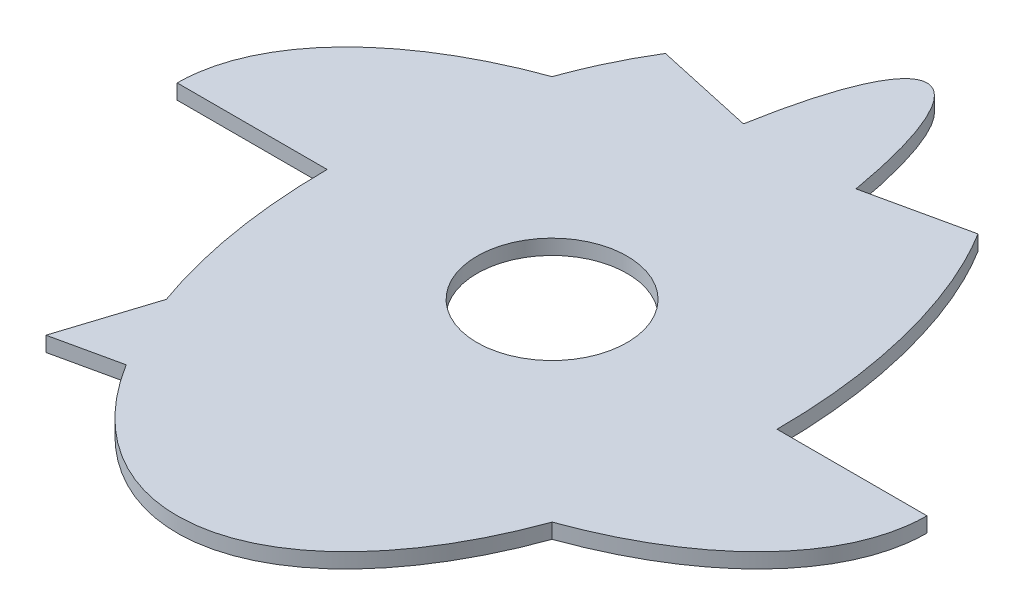
SolidWorks part; units mm, degrees
material "1.4016 (X6Cr17)"
ref_plane "Płaszczyzna przednia" through (0, 0, 0) normal (0, 0, 1) x (1, 0, 0)
ref_plane "Płaszczyzna górna" through (0, 0, 0) normal (0, 1, 0) x (1, 0, 0)
ref_plane "Płaszczyzna prawa" through (0, 0, 0) normal (1, 0, 0) x (0, 0, -1)
sketch "Szkic1" plane through (0, 0, 0) normal (0, 1, 0) x (1, 0, 0)
  line L0 (-61.0765, 17.9546) -> (45.7753, 41.4402)
  line L1 (-50, 0) -> (50, 0)
  line L2 (0, 50) -> (0, -50)
  line L3 (61.0765, 17.9546) -> (-45.7753, 41.4402)
  line L4 (-61.0765, -17.9546) -> (45.7753, -41.4402)
  line L5 (61.0765, -17.9546) -> (-45.7753, -41.4402)
  line L6 (34.2973, 52.5744) -> (-2.1147, -61.4701)
  line L7 (-34.2973, 52.5744) -> (2.1147, -61.4701)
  line L8 (34.2973, -52.5744) -> (-2.1147, 61.4701)
  line L9 (-34.2973, -52.5744) -> (2.1147, 61.4701)
  circle A0 centre (0, 0) radius 50
  circle A1 centre (0, 0) radius 30
  circle A2 centre (0, 0) radius 10
  ellipse E0 centre (0, 0) end of major axis (0, 50) minor radius 10
  ellipse E1 centre (0, 0) end of major axis (0, -50) minor radius 30
  ellipse E2 centre (0, 0) end of major axis (50, 0) minor radius 30
  point P5 (-25.7248, 25.7248)
  point P20 (-8.0582, 29.6078)
  point P34 (25.7248, -25.7248)
  point P39 (8.0582, -29.6078)
  point P41 (25.7248, 25.7248)
  dimension "D1" = 100
  dimension "D2" = 60
  dimension "D3" = 20
extrude "Dodanie-wyciągnięcie1" add sketch "Szkic1" along normal blind 2
